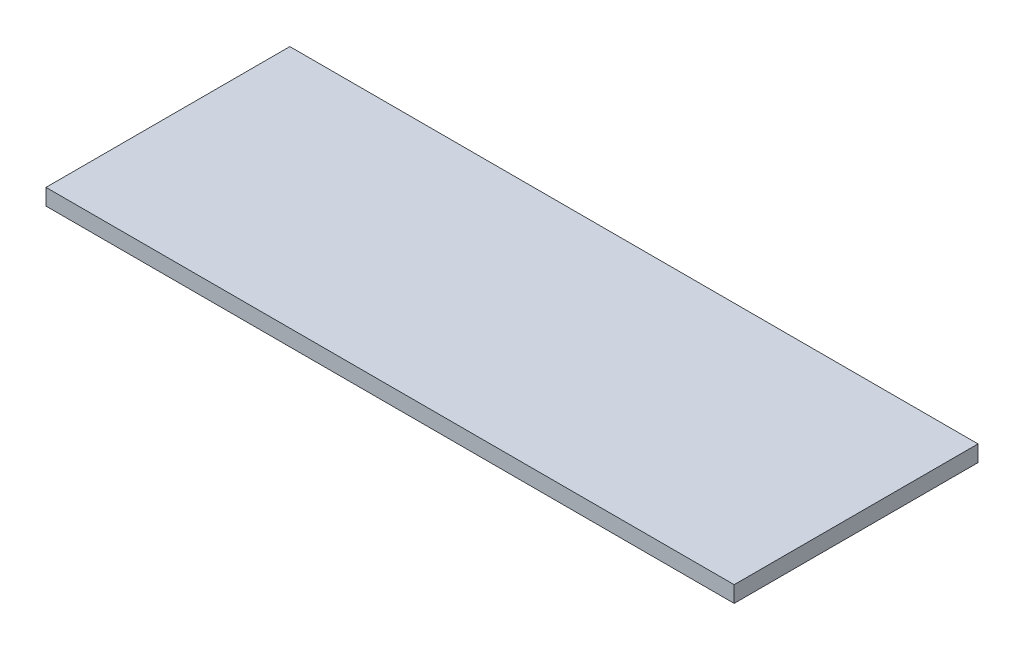
SolidWorks part; units mm, degrees
material "Бальса"
ref_plane "Спереди" through (0, 0, 0) normal (0, 0, 1) x (1, 0, 0)
ref_plane "Сверху" through (0, 0, 0) normal (0, 1, 0) x (1, 0, 0)
ref_plane "Справа" through (0, 0, 0) normal (1, 0, 0) x (0, 0, -1)
sketch "Эскиз1" plane through (0, 0, 0) normal (0, 1, 0) x (1, 0, 0)
  line L1 (0, 0) -> (1270, 0)
  line L2 (0, 0) -> (0, 450)
  line L3 (0, 450) -> (1270, 450)
  line L4 (1270, 0) -> (1270, 450)
  dimension "D1" = 1270
  dimension "D2" = 450
extrude "Бобышка-Вытянуть1" add sketch "Эскиз1" along normal blind 30
sketch "Эскиз2" [suppressed] plane through (0, 0, 0) normal (0, -1, 0) x (1, 0, 0)
  line L0 (516.7576, -15) -> (516.7576, 15) construction
  line L1 (129.2576, -15) -> (904.2576, -15)
  line L2 (129.2576, -15) -> (129.2576, -410)
  line L3 (129.2576, -410) -> (904.2576, -410)
  line L4 (904.2576, -15) -> (904.2576, -410)
  line L5 (159.2576, 15) -> (874.2576, 15) construction
  line L6 (904.2576, -212.5) -> (874.2576, -212.5) construction
  line L7 (874.2576, -440) -> (874.2576, 15) construction
  dimension "D1" = 30
extrude "Вырез-Вытянуть1" [suppressed] cut sketch "Эскиз2" against normal through all
